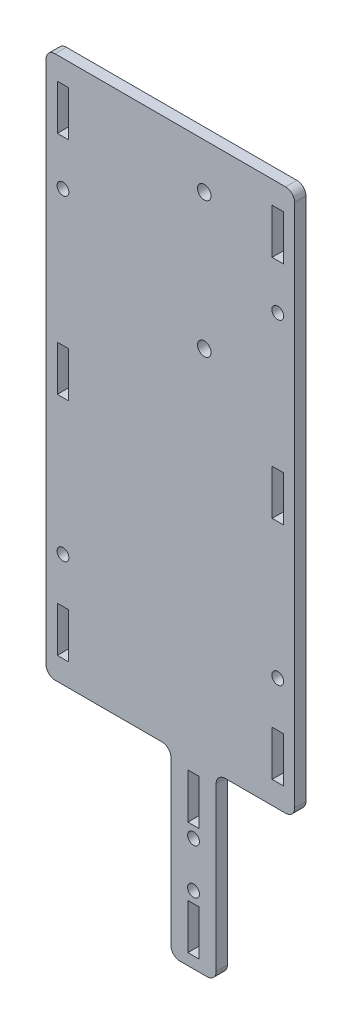
SolidWorks part; units mm, degrees
ref_plane "Front Plane" through (0, 0, 0) normal (0, 0, 1) x (1, 0, 0)
ref_plane "Top Plane" through (0, 0, 0) normal (0, 1, 0) x (1, 0, 0)
ref_plane "Right Plane" through (0, 0, 0) normal (1, 0, 0) x (0, 0, -1)
sketch "Sketch1" plane through (0, 0, 0) normal (0, 0, 1) x (1, 0, 0)
  line L0 (41.4375, -50.8) -> (41.4375, 0) construction
  line L1 (0, 0) -> (69.85, 0)
  line L2 (0, 0) -> (0, 152.4)
  line L3 (0, 152.4) -> (69.85, 152.4)
  line L4 (69.85, 0) -> (69.85, 152.4)
  line L5 (35.0875, 0) -> (47.7875, 0)
  line L6 (35.0875, 0) -> (35.0875, -50.8)
  line L7 (35.0875, -50.8) -> (47.7875, -50.8)
  line L8 (47.7875, 0) -> (47.7875, -50.8)
  line L9 (35.0875, -25.4) -> (47.7875, -25.4) construction
  line L10 (39.85, -34.925) -> (43.025, -34.925)
  line L11 (39.85, -34.925) -> (39.85, -47.625)
  line L12 (39.85, -47.625) -> (43.025, -47.625)
  line L13 (43.025, -34.925) -> (43.025, -47.625)
  line L14 (39.85, -34.925) -> (43.025, -47.625) construction
  line L15 (39.85, -47.625) -> (43.025, -34.925) construction
  line L16 (39.85, -3.175) -> (43.025, -15.875) construction
  line L17 (39.85, -15.875) -> (43.025, -3.175) construction
  line L18 (43.025, -15.875) -> (43.025, -3.175)
  line L19 (39.85, -3.175) -> (43.025, -3.175)
  line L20 (39.85, -15.875) -> (39.85, -3.175)
  line L21 (39.85, -15.875) -> (43.025, -15.875)
  point P11 (41.4375, -41.275)
  point P22 (41.4375, -9.525)
  dimension "D1" = 69.85
  dimension "D2" = 152.4
  dimension "D3" = 50.8
  dimension "D4" = 12.7
  dimension "D5" = 3.175
  dimension "D6" = 19.05
  dimension "D7" = 12.7
  dimension "D8" = 30
extrude "Boss-Extrude1" add sketch "Sketch1" along normal blind 3.175 contours L1 L4 L3 L2 | L8 L1 L6 L7 L21 L20 L19 L18 L10 L13 L12 L11
sketch "Sketch3" plane through (0, 0, 3.175) normal (0, 0, 1) x (1, 0, 0)
  line L0 (34.925, 152.4) -> (34.925, 0) construction
  line L1 (0, 76.2) -> (69.85, 76.2) construction
  line L2 (4.7625, 19.05) -> (4.7625, 133.35) construction
  line L3 (3.175, 146.05) -> (6.35, 146.05)
  line L4 (3.175, 146.05) -> (3.175, 133.35)
  line L5 (3.175, 133.35) -> (6.35, 133.35)
  line L6 (6.35, 146.05) -> (6.35, 133.35)
  line L7 (3.175, 19.05) -> (6.35, 19.05)
  line L8 (0, 0) -> (35.0875, 0)
  line L9 (35.0875, 0) -> (35.0875, -50.8)
  line L10 (35.0875, -50.8) -> (47.7875, -50.8)
  line L11 (47.7875, -50.8) -> (47.7875, 0)
  line L12 (47.7875, 0) -> (69.85, 0)
  line L13 (69.85, 0) -> (69.85, 152.4)
  line L14 (69.85, 152.4) -> (0, 152.4)
  line L15 (0, 152.4) -> (0, 0)
  line L16 (0, 0) -> (35.0875, 0)
  line L17 (35.0875, 0) -> (35.0875, -50.8)
  line L18 (35.0875, -50.8) -> (47.7875, -50.8)
  line L19 (47.7875, -50.8) -> (47.7875, 0)
  line L20 (47.7875, 0) -> (69.85, 0)
  line L21 (69.85, 0) -> (69.85, 152.4)
  line L22 (69.85, 152.4) -> (0, 152.4)
  line L23 (0, 152.4) -> (0, 0)
  line L24 (3.175, 19.05) -> (3.175, 6.35)
  line L25 (3.175, 6.35) -> (6.35, 6.35)
  line L26 (6.35, 19.05) -> (6.35, 6.35)
  line L27 (3.175, 82.55) -> (6.35, 82.55)
  line L28 (3.175, 82.55) -> (3.175, 69.85)
  line L29 (3.175, 69.85) -> (6.35, 69.85)
  line L30 (6.35, 82.55) -> (6.35, 69.85)
  line L31 (3.175, 82.55) -> (6.35, 69.85) construction
  line L32 (3.175, 69.85) -> (6.35, 82.55) construction
  line L33 (66.675, 69.85) -> (63.5, 82.55) construction
  line L34 (66.675, 82.55) -> (63.5, 69.85) construction
  line L35 (65.0875, 19.05) -> (65.0875, 133.35) construction
  line L36 (63.5, 82.55) -> (63.5, 69.85)
  line L37 (66.675, 69.85) -> (63.5, 69.85)
  line L38 (66.675, 82.55) -> (66.675, 69.85)
  line L39 (66.675, 82.55) -> (63.5, 82.55)
  line L40 (63.5, 19.05) -> (63.5, 6.35)
  line L41 (66.675, 6.35) -> (63.5, 6.35)
  line L42 (66.675, 19.05) -> (66.675, 6.35)
  line L43 (66.675, 19.05) -> (63.5, 19.05)
  line L44 (63.5, 146.05) -> (63.5, 133.35)
  line L45 (66.675, 133.35) -> (63.5, 133.35)
  line L46 (66.675, 146.05) -> (66.675, 133.35)
  line L47 (66.675, 146.05) -> (63.5, 146.05)
  circle A0 centre (4.7625, 120.65) radius 1.651
  circle A1 centre (4.7625, 31.75) radius 1.651
  circle A2 centre (65.0875, 31.75) radius 1.651
  circle A3 centre (65.0875, 120.65) radius 1.651
  point P20 (4.7625, 76.2)
  point P49 (65.0875, 76.2)
  dimension "D7" = 3.302
  dimension "D2" = 12.7
  dimension "D3" = 3.175
  dimension "D4" = 6.35
  dimension "D5" = 6.35
  dimension "D6" = 3.175
  dimension "D8" = 12.7
  dimension "D1" = 0
extrude "Cut-Extrude3" cut sketch "Sketch3" against normal blind 3.175 contours L6 L3 L4 L5 | L26 L7 L24 L25 | L46 L47 L44 L45 | A0 | L27 L30 L29 L28 | A1 | L40 L41 L42 L43 | A2 | A3 | L36 L37 L38 L39
sketch "Sketch4" plane through (0, 0, 3.175) normal (0, 0, 1) x (1, 0, 0)
  line L0 (41.4375, -15.875) -> (41.4375, -34.925) construction
  line L1 (39.85, -15.875) -> (43.025, -15.875) construction
  line L2 (39.85, -34.925) -> (43.025, -34.925) construction
  line L3 (35.0875, -25.4) -> (47.7875, -25.4) construction
  line L4 (35.0875, 0) -> (35.0875, -50.8) construction
  line L5 (47.7875, 0) -> (47.7875, -50.8) construction
  circle A0 centre (41.4375, -19.05) radius 1.651
  circle A1 centre (41.4375, -31.75) radius 1.651
  dimension "D1" = 3.302
  dimension "D2" = 12.7
extrude "Cut-Extrude4" cut sketch "Sketch4" against normal blind 3.175
fillet "Fillet1" radius 2.54 8 edges at (69.85, 152.4, 1.5875) (69.85, 0, 1.5875) (47.7875, 0, 1.5875) (47.7875, -50.8, 1.5875) (35.0875, -50.8, 1.5875) (35.0875, 0, 1.5875) (0, 0, 1.5875) (0, 152.4, 1.5875)
sketch "Sketch5" plane through (0, 0, 3.175) normal (0, 0, 1) x (1, 0, 0)
  line L0 (44.45, 152.4) -> (44.45, 0) construction
  line L1 (2.54, 152.4) -> (67.31, 152.4) construction
  line L2 (50.3275, 0) -> (67.31, 0) construction
  line L3 (69.85, 2.54) -> (69.85, 149.86) construction
  circle A0 centre (44.45, 139.7) radius 1.905
  circle A1 centre (44.45, 101.6) radius 1.905
  dimension "D2" = 3.81
  dimension "D1" = 25.4
  dimension "D3" = 38.1
  dimension "D4" = 12.7
extrude "Cut-Extrude5" cut sketch "Sketch5" against normal blind 3.175
